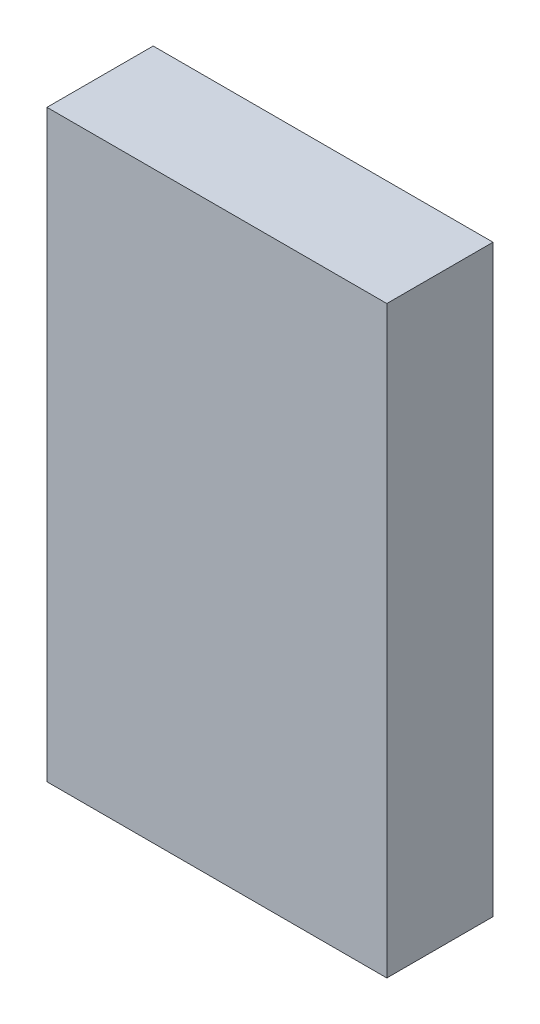
SolidWorks part; units mm, degrees
ref_plane "Plan de face" through (0, 0, 0) normal (0, 0, 1) x (1, 0, 0)
ref_plane "Plan de dessus" through (0, 0, 0) normal (0, 1, 0) x (1, 0, 0)
ref_plane "Plan de droite" through (0, 0, 0) normal (1, 0, 0) x (0, 0, -1)
sketch "Esquisse1" plane through (0, 0, 0) normal (0, 0, 1) x (1, 0, 0)
  line L1 (0, 0) -> (32, 0)
  line L2 (0, 0) -> (0, 55)
  line L3 (0, 55) -> (32, 55)
  line L4 (32, 0) -> (32, 55)
  dimension "D1" = 32
  dimension "D2" = 55
extrude "Extrusion1" add sketch "Esquisse1" along normal blind 10
